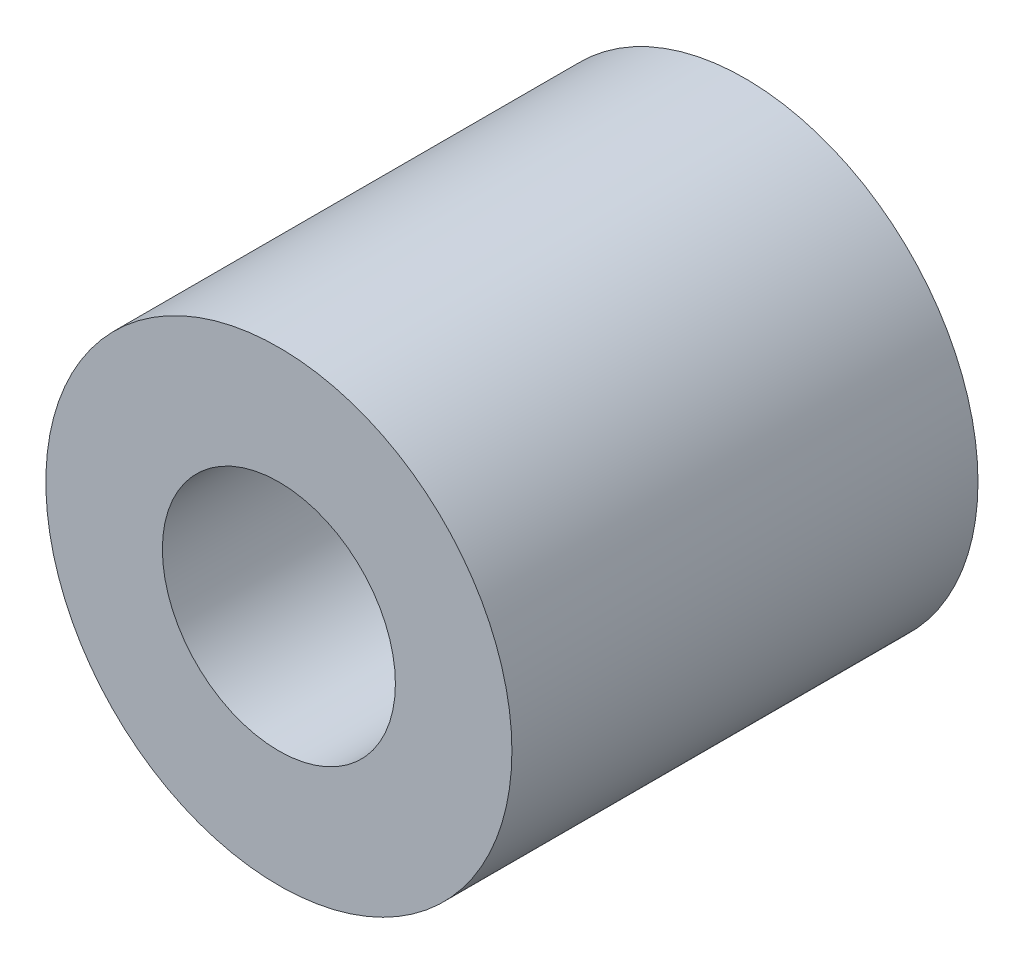
SolidWorks part; units mm, degrees
ref_plane "前视基准面" through (0, 0, 0) normal (0, 0, 1) x (1, 0, 0)
ref_plane "上视基准面" through (0, 0, 0) normal (0, 1, 0) x (1, 0, 0)
ref_plane "右视基准面" through (0, 0, 0) normal (1, 0, 0) x (0, 0, -1)
other "Configuration Table"
sketch "草图1" plane through (0, 0, 0) normal (0, 0, 1) x (1, 0, 0)
  circle A0 centre (0, 0) radius 2.5
  circle A1 centre (0, 0) radius 1.25
  dimension "D1" = 5
  dimension "D2" = 2.5
extrude "凸台-拉伸1" add sketch "草图1" along normal blind 5
